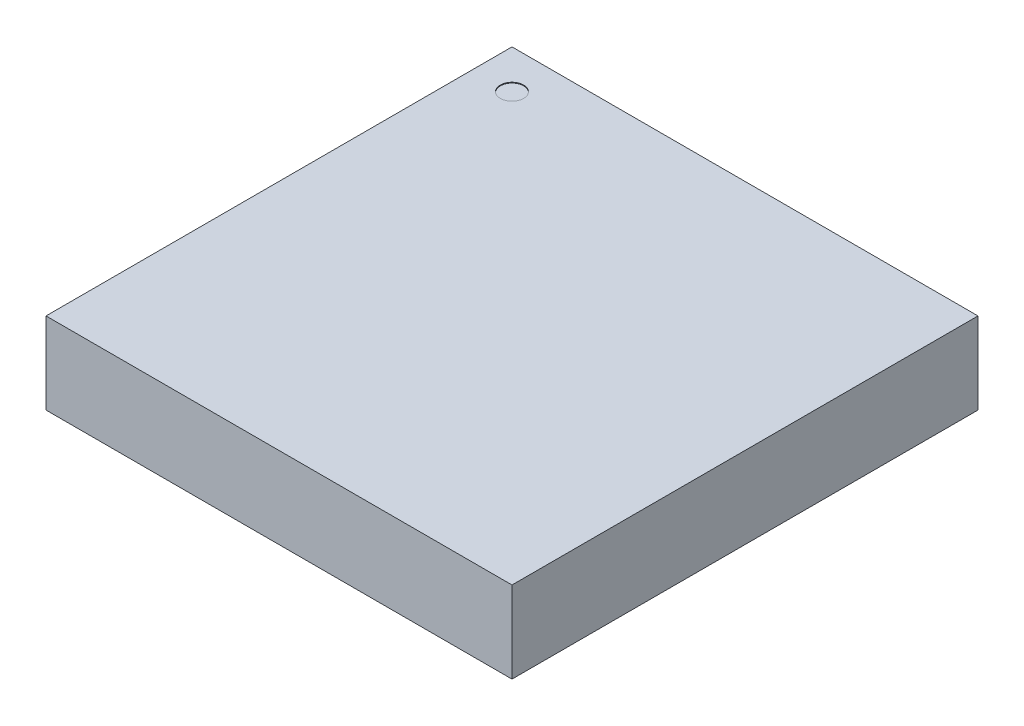
SolidWorks part; units mm, degrees
ref_plane "Front Plane" through (0, 0, 0) normal (0, 0, 1) x (1, 0, 0)
ref_plane "Top Plane" through (0, 0, 0) normal (0, 1, 0) x (1, 0, 0)
ref_plane "Right Plane" through (0, 0, 0) normal (1, 0, 0) x (0, 0, -1)
sketch "Sketch1" plane through (0, 0, 0) normal (0, 1, 0) x (1, 0, 0)
  line L1 (-2.2835, 2.8995) -> (3.7165, 2.8995)
  line L2 (-2.2835, 2.8995) -> (-2.2835, -3.1005)
  line L3 (-2.2835, -3.1005) -> (3.7165, -3.1005)
  line L4 (3.7165, 2.8995) -> (3.7165, -3.1005)
  dimension "D1" = 6
  dimension "D2" = 6
extrude "Boss-Extrude1" add sketch "Sketch1" along normal blind 1.05
sketch "Sketch2" plane through (0, 1.05, 0) normal (0, 1, 0) x (1, 0, 0)
  line L0 (-2.2835, 2.8995) -> (-2.2835, -3.1005) construction
  line L1 (3.7165, 2.8995) -> (-2.2835, 2.8995) construction
  circle A0 centre (-1.7835, 2.3995) radius 0.15
  dimension "D3" = 0.3
  dimension "D1" = 0.5
  dimension "D2" = 0.5
extrude "Cut-Extrude1" cut sketch "Sketch2" against normal blind 0.01 contours A0
